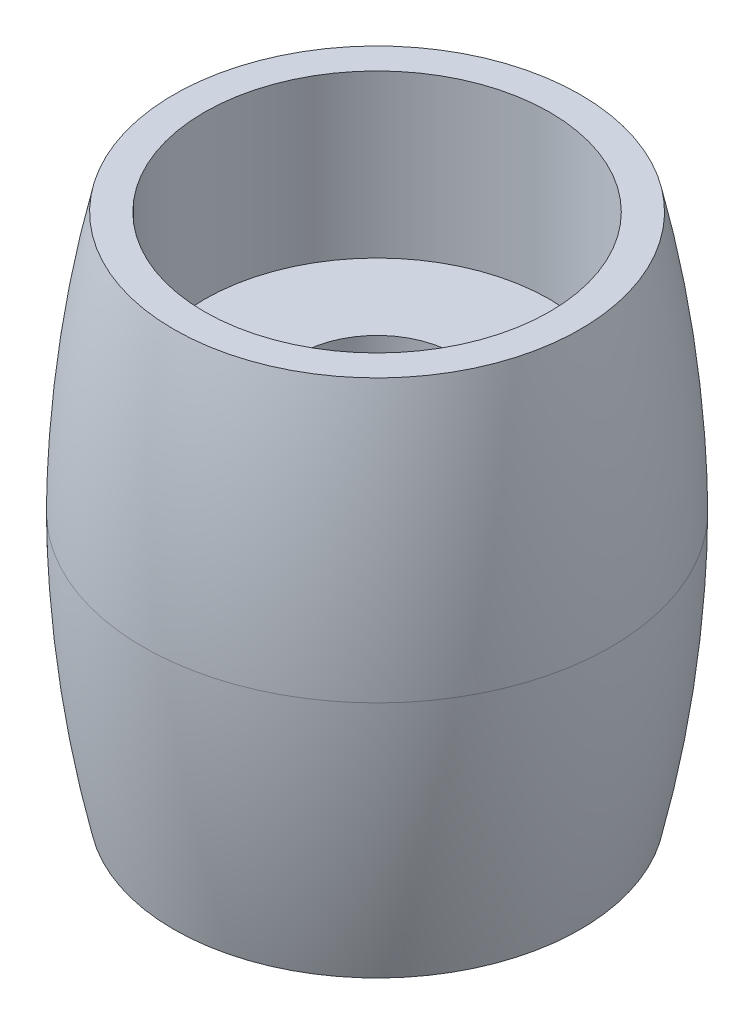
SolidWorks part; units mm, degrees
ref_plane "Front Plane" through (0, 0, 0) normal (0, 0, 1) x (1, 0, 0)
ref_plane "Top Plane" through (0, 0, 0) normal (0, 1, 0) x (1, 0, 0)
ref_plane "Right Plane" through (0, 0, 0) normal (1, 0, 0) x (0, 0, -1)
sketch "Sketch1" plane through (0, 0, 0) normal (0, 0, 1) x (1, 0, 0)
  line L0 (0, -14.5711) -> (0, 19.3261) construction
  line L10 (5.65, -3.2) -> (2.55, -3.2)
  line L11 (6.65, -8.5) -> (5.65, -8.5)
  line L12 (5.65, -8.5) -> (5.65, -3.2)
  line L20 (2.55, -3.2) -> (2.55, 0)
  line L21 (2.55, 0) -> (7.65, 0)
  arc A0 (7.65, 0) -> (6.65, -8.5) centre (-32.348, 0.3968) cw
  dimension "D6" = 40
  dimension "D1" = 1
  dimension "D2" = 8.5
  dimension "D3" = 5.3
  dimension "D4" = 1
  dimension "D5" = 5.1
  dimension "10" = 11.3
revolve "Revolve1" add sketch "Sketch1" angle 360 about L0
mirror "Mirror1" about plane through (2.55, 0, 0) normal (0, 1, 0) of "Revolve1"
